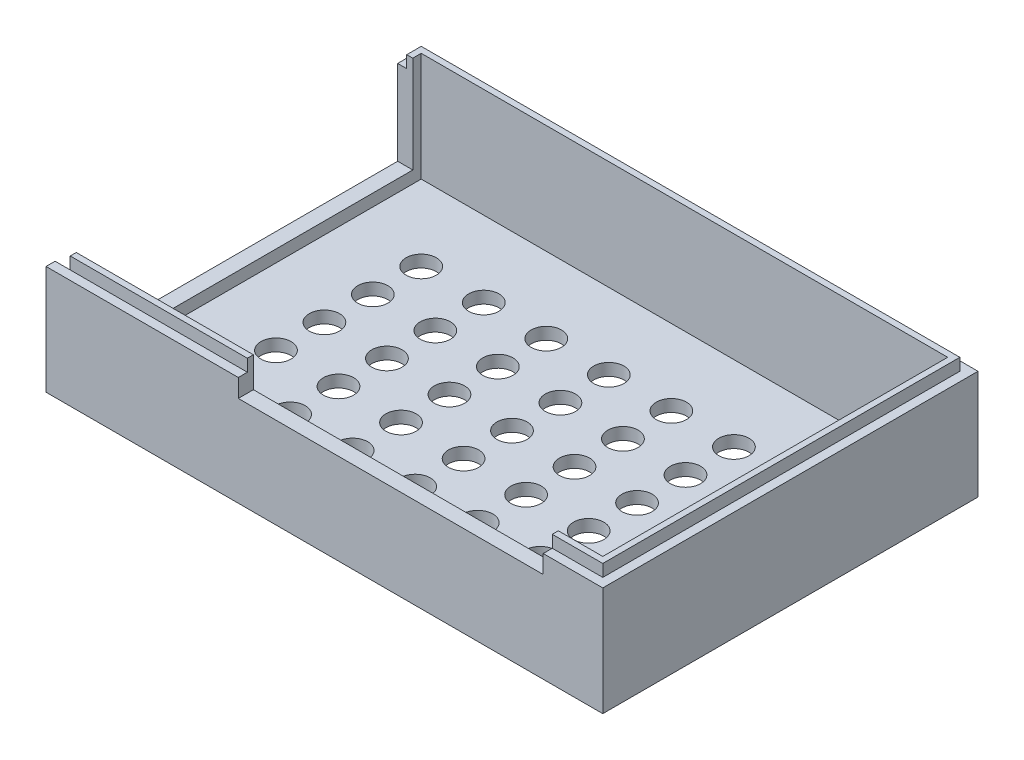
SolidWorks part; units mm, degrees
material "ABS"
ref_plane "Front" through (0, 0, 0) normal (0, 0, 1) x (1, 0, 0)
ref_plane "Top" through (0, 0, 0) normal (0, 1, 0) x (1, 0, 0)
ref_plane "Right" through (0, 0, 0) normal (1, 0, 0) x (0, 0, -1)
sketch "Croquis1" plane through (0, 0, 0) normal (0, 1, 0) x (1, 0, 0)
  line L1 (-46, -31) -> (46, -31)
  line L2 (-46, -31) -> (-46, 31)
  line L3 (-46, 31) -> (46, 31)
  line L4 (46, -31) -> (46, 31)
  line L5 (-46, -31) -> (46, 31) construction
  line L6 (-46, 31) -> (46, -31) construction
  point P0 (0, 0)
  dimension "D1" = 92
  dimension "D2" = 62
extrude "Saliente-Extruir1" add sketch "Croquis1" along normal blind 18
sketch "Croquis2" plane through (0, 18, 0) normal (0, 1, 0) x (1, 0, 0)
  line L0 (46, 31) -> (-46, 31) construction
  line L1 (-43.5, -28.5) -> (43.5, -28.5)
  line L2 (-43.5, -28.5) -> (-43.5, 28.5)
  line L3 (-43.5, 28.5) -> (43.5, 28.5)
  line L4 (43.5, -28.5) -> (43.5, 28.5)
  line L5 (-43.5, -28.5) -> (43.5, 28.5) construction
  line L6 (-43.5, 28.5) -> (43.5, -28.5) construction
  line L7 (-46, 31) -> (-46, -31) construction
  point P0 (0, 0)
  dimension "D1" = 2.5
  dimension "D2" = 2.5
extrude "Cortar-Extruir1" cut sketch "Croquis2" against normal blind 16
sketch "Croquis3" plane through (0, 18, 0) normal (0, 1, 0) x (1, 0, 0)
  line L1 (-43.5, -28.5) -> (43.5, -28.5)
  line L2 (-43.5, -28.5) -> (-43.5, 28.5)
  line L3 (-43.5, 28.5) -> (43.5, 28.5)
  line L4 (43.5, -28.5) -> (43.5, 28.5)
  line L5 (-43.5, -28.5) -> (43.5, 28.5) construction
  line L6 (-43.5, 28.5) -> (43.5, -28.5) construction
  line L7 (-44.5, -29.5) -> (44.5, -29.5)
  line L8 (-44.5, -29.5) -> (-44.5, 29.5)
  line L9 (-44.5, 29.5) -> (44.5, 29.5)
  line L10 (44.5, -29.5) -> (44.5, 29.5)
  line L11 (-44.5, -29.5) -> (44.5, 29.5) construction
  line L12 (-44.5, 29.5) -> (44.5, -29.5) construction
  point P0 (0, 0)
  point P7 (0, 0)
  dimension "D1" = 1
  dimension "D2" = 1
extrude "Saliente-Extruir2" add sketch "Croquis3" along normal blind 2
sketch "Croquis4" plane through (0, 20, 0) normal (0, 1, 0) x (1, 0, 0)
  line L0 (-46, 31) -> (-46, -31) construction
  line L1 (-46, -25.5516) -> (-43.5, -25.5516)
  line L2 (-46, -25.5516) -> (-46, -11.4015)
  line L3 (-46, -11.4015) -> (-43.5, -11.4015)
  line L4 (-43.5, -25.5516) -> (-43.5, -11.4015)
  line L5 (-43.5, 28.5) -> (-43.5, -28.5) construction
  line L6 (-28.8211, -25.0516) -> (-47.1776, -25.0516) construction
  line L7 (-46, -7.4776) -> (-43.5, -7.4776)
  line L8 (-46, -7.4776) -> (-46, 6.5224)
  line L9 (-46, 6.5224) -> (-43.5, 6.5224)
  line L10 (-43.5, -7.4776) -> (-43.5, 6.5224)
  line L11 (-46, 10.0965) -> (-43.5, 10.0965)
  line L12 (-46, 10.0965) -> (-46, 27.1057)
  line L13 (-46, 27.1057) -> (-43.5, 27.1057)
  line L14 (-43.5, 10.0965) -> (-43.5, 27.1057)
  line L15 (-47.1776, -11.9015) -> (-28.8211, -11.9015) construction
  line L16 (-28.8211, -6.9776) -> (-47.1776, -6.9776) construction
  line L17 (-47.1776, 6.0224) -> (-28.8211, 6.0224) construction
  line L18 (-24.6082, 10.5965) -> (-46.2146, 10.5965) construction
  line L19 (-46.2146, 26.6057) -> (-24.6082, 26.6057) construction
  dimension "D1" = 0.5
  dimension "D2" = 0.5
  dimension "D3" = 0.5
  dimension "D4" = 0.5
  dimension "D5" = 0.5
  dimension "D6" = 0.5
extrude "Cortar-Extruir2" cut sketch "Croquis4" against normal blind 16
sketch "Croquis5" plane through (0, 20, 0) normal (0, 1, 0) x (1, 0, 0)
  line L0 (-43.5, -28.5) -> (43.5, -28.5) construction
  line L1 (36.1586, -28.5) -> (26.1932, -28.5)
  line L2 (36.1586, -28.5) -> (36.1586, -31)
  line L3 (36.1586, -31) -> (26.1932, -31)
  line L4 (26.1932, -28.5) -> (26.1932, -31)
  line L5 (-46, -31) -> (46, -31) construction
  line L6 (35.6586, -21.2292) -> (35.6586, -28.9255) construction
  line L7 (26.6932, -28.9255) -> (26.6932, -21.2292) construction
  line L8 (-43.5, -28.5) -> (43.5, -28.5) construction
  line L9 (19.8422, -28.5) -> (12.5375, -28.5)
  line L10 (19.8422, -28.5) -> (19.8422, -31)
  line L11 (19.8422, -31) -> (12.5375, -31)
  line L12 (12.5375, -28.5) -> (12.5375, -31)
  line L13 (19.3422, -20.626) -> (19.3422, -28.6409) construction
  line L14 (13.0375, -28.6409) -> (13.0375, -23.8845) construction
  line L17 (6.2881, -28.5) -> (-1.1323, -28.5)
  line L18 (6.2881, -28.5) -> (6.2881, -31)
  line L19 (6.2881, -31) -> (-1.1323, -31)
  line L20 (-1.1323, -28.5) -> (-1.1323, -31)
  line L21 (5.7881, -20.626) -> (5.7881, -28.6409) construction
  line L22 (-0.6323, -28.6409) -> (-0.6323, -20.626) construction
  line L24 (-9.2258, -28.5) -> (-14.2258, -28.5)
  line L25 (-9.2258, -28.5) -> (-9.2258, -31)
  line L26 (-9.2258, -31) -> (-14.2258, -31)
  line L27 (-14.2258, -28.5) -> (-14.2258, -31)
  line L30 (-14.2258, -31) -> (-14.2258, -29.5) construction
  line L31 (-9.2258, -29.5) -> (-9.2258, -31) construction
  dimension "D1" = 0.5
  dimension "D2" = 0.5
  dimension "D3" = 0.5
  dimension "D4" = 0.5
  dimension "D5" = 0.5
  dimension "D6" = 0.5
extrude "Cortar-Extruir3" cut sketch "Croquis5" against normal blind 5
sketch "Croquis7" plane through (0, 0, 0) normal (0, -1, 0) x (1, 0, 0)
  line L0 (46, -31) -> (-46, -31) construction
  line L1 (46, 31) -> (46, -31) construction
  line L2 (-46, 31) -> (46, 31) construction
  line L3 (-46, -31) -> (-46, 31) construction
  line L4 (20.6667, -16) -> (20.6667, 16) construction
  circle A1 centre (31, -16) radius 2.5
  circle A2 centre (20.6667, -16) radius 2.5
  circle A3 centre (10.3333, -16) radius 2.5
  circle A4 centre (0, -16) radius 2.5
  circle A5 centre (-10.3333, -16) radius 2.5
  circle A6 centre (-20.6667, -16) radius 2.5
  circle A7 centre (-31, -16) radius 2.5
  circle A8 centre (20.6667, -8) radius 2.5
  circle A9 centre (10.3333, -8) radius 2.5
  circle A10 centre (0, -8) radius 2.5
  circle A11 centre (-10.3333, -8) radius 2.5
  circle A12 centre (-20.6667, -8) radius 2.5
  circle A13 centre (-31, -8) radius 2.5
  circle A14 centre (20.6667, 0) radius 2.5
  circle A15 centre (10.3333, 0) radius 2.5
  circle A16 centre (0, 0) radius 2.5
  circle A17 centre (-10.3333, 0) radius 2.5
  circle A18 centre (-20.6667, 0) radius 2.5
  circle A19 centre (-31, 0) radius 2.5
  circle A20 centre (20.6667, 8) radius 2.5
  circle A21 centre (10.3333, 8) radius 2.5
  circle A22 centre (0, 8) radius 2.5
  circle A23 centre (-10.3333, 8) radius 2.5
  circle A24 centre (-20.6667, 8) radius 2.5
  circle A25 centre (-31, 8) radius 2.5
  circle A26 centre (20.6667, 16) radius 2.5
  circle A27 centre (10.3333, 16) radius 2.5
  circle A28 centre (0, 16) radius 2.5
  circle A29 centre (-10.3333, 16) radius 2.5
  circle A30 centre (-20.6667, 16) radius 2.5
  circle A31 centre (-31, 16) radius 2.5
  circle A32 centre (31, -8) radius 2.5
  circle A33 centre (31, 0) radius 2.5
  circle A34 centre (31, 8) radius 2.5
  circle A35 centre (31, 16) radius 2.5
  dimension "D1" = 5
  dimension "D2" = 15
  dimension "D3" = 15
  dimension "D7" = 15
  dimension "D6" = 15
  dimension "D4" = 7
  dimension "D5" = 5
extrude "Cortar-Extruir4" cut sketch "Croquis7" against normal up to surface (2 mm away) up to face at (0, 2, 0)
sketch "Croquis8" plane through (0, 0, 31) normal (0, 0, 1) x (1, 0, 0)
  line L0 (36.1586, 20) -> (44.5, 20) construction
  line L1 (-14.2258, 15) -> (36.1586, 15)
  line L2 (-14.2258, 15) -> (-14.2258, 20)
  line L3 (-14.2258, 20) -> (36.1586, 20)
  line L4 (36.1586, 15) -> (36.1586, 20)
  line L5 (12.5375, 15) -> (19.8422, 15) construction
  line L6 (36.1586, 15) -> (36.1586, 18) construction
extrude "Cortar-Extruir5" cut sketch "Croquis8" against normal up to surface (2.5 mm away) up to face at (7.6436, 16.2, 28.5)
sketch "Croquis9" plane through (-46, 0, 0) normal (-1, 0, 0) x (0, 0, 1)
  line L0 (25.5516, 20) -> (29.5, 20) construction
  line L1 (-27.1057, 4) -> (29.5, 4)
  line L2 (-27.1057, 4) -> (-27.1057, 20)
  line L3 (-27.1057, 20) -> (29.5, 20)
  line L4 (29.5, 4) -> (29.5, 20)
  line L6 (-27.1057, 4) -> (-10.0965, 4) construction
  line L7 (29.5, 20) -> (29.5, 18) construction
extrude "Cortar-Extruir6" cut sketch "Croquis9" against normal up to surface (2.5 mm away) up to face at (-43.5, 11.75, 0.0883)
